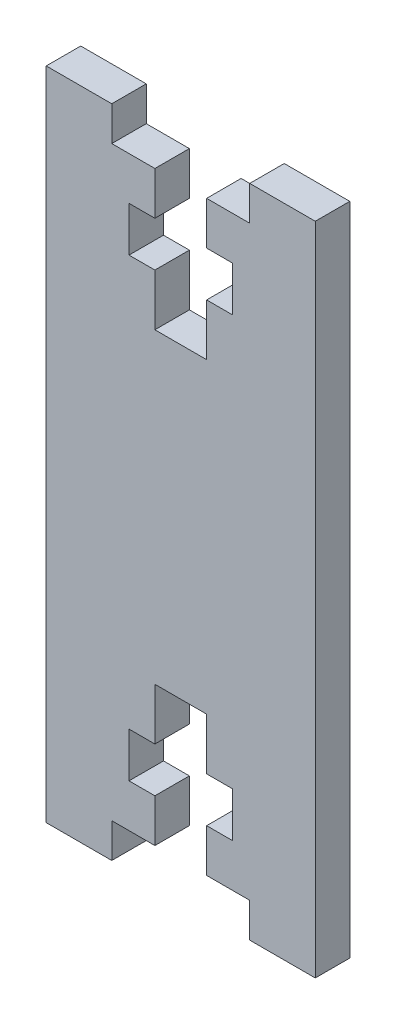
SolidWorks part; units mm, degrees
ref_plane "前视基准面" through (0, 0, 0) normal (0, 0, 1) x (1, 0, 0)
ref_plane "上视基准面" through (0, 0, 0) normal (0, 1, 0) x (1, 0, 0)
ref_plane "右视基准面" through (0, 0, 0) normal (1, 0, 0) x (0, 0, -1)
sketch "草图2" plane through (0, 0, 0) normal (0, 0, 1) x (1, 0, 0)
  line L12 (2, -29.5) -> (2, 8.5) construction
  line L18 (6, -27.5) -> (6, -29.5)
  line L19 (6, -29.5) -> (9.8, -29.5)
  line L20 (9.8, 8.5) -> (9.8, -29.5)
  line L21 (-2, -29.5) -> (-5.8, -29.5)
  line L22 (-2, -27.5) -> (-2, -29.5)
  line L23 (-5.8, -29.5) -> (-5.8, 8.5)
  line L24 (3.5, -25) -> (3.5, -27.5)
  line L25 (-2, -27.5) -> (0.5, -27.5)
  line L29 (2, -10.5) -> (4.7487, -10.5) construction
  line L33 (-2, 8.5) -> (-5.8, 8.5)
  line L34 (-2, 6.5) -> (0.5, 6.5)
  line L35 (3.5, 6.5) -> (6, 6.5)
  line L36 (6, 8.5) -> (9.8, 8.5)
  line L37 (-2, 8.5) -> (-2, 6.5)
  line L38 (6, 8.5) -> (6, 6.5)
  line L39 (-1, 4) -> (-1, 1.4)
  line L40 (-1, 1.4) -> (0.5, 1.4)
  line L41 (0.5, 1.4) -> (0.5, -1.6)
  line L42 (3.5, 1.4) -> (3.5, -1.6)
  line L43 (5, 1.4) -> (3.5, 1.4)
  line L44 (5, 4) -> (5, 1.4)
  line L45 (0.5, 4) -> (-1, 4)
  line L46 (0.5, -1.6) -> (3.5, -1.6)
  line L47 (3.5, 4) -> (5, 4)
  line L48 (0.5, 4) -> (0.5, 6.5)
  line L49 (3.5, 4) -> (3.5, 6.5)
  line L50 (3.5, -27.5) -> (6, -27.5)
  line L51 (5, -25) -> (5, -22.4)
  line L52 (5, -22.4) -> (3.5, -22.4)
  line L53 (3.5, -22.4) -> (3.5, -19.4)
  line L54 (0.5, -22.4) -> (0.5, -19.4)
  line L55 (-1, -22.4) -> (0.5, -22.4)
  line L56 (-1, -25) -> (-1, -22.4)
  line L57 (3.5, -25) -> (5, -25)
  line L58 (3.5, -19.4) -> (0.5, -19.4)
  line L59 (0.5, -25) -> (-1, -25)
  line L61 (0.5, -25) -> (0.5, -27.5)
  point P5 (2, -27.5)
extrude "凸台-拉伸1" add sketch "草图2" along normal blind 2
sketch "草图3" plane through (0, -27.5, 0) normal (0, -1, 0) x (1, 0, 0)
  line L0 (0.5, 1) -> (3.5, 1)
  line L1 (0.5, 2) -> (0.5, 0) construction
  line L2 (3.5, 2) -> (3.5, 0) construction
  circle A0 centre (2, 1) radius 1.5
sketch "草图4" plane through (0, 6.5, 0) normal (0, 1, 0) x (1, 0, 0)
  line L0 (0.5, -1) -> (3.5, -1)
  line L1 (0.5, -2) -> (0.5, 0) construction
  line L2 (3.5, -2) -> (3.5, 0) construction
  circle A0 centre (2, -1) radius 1.5
